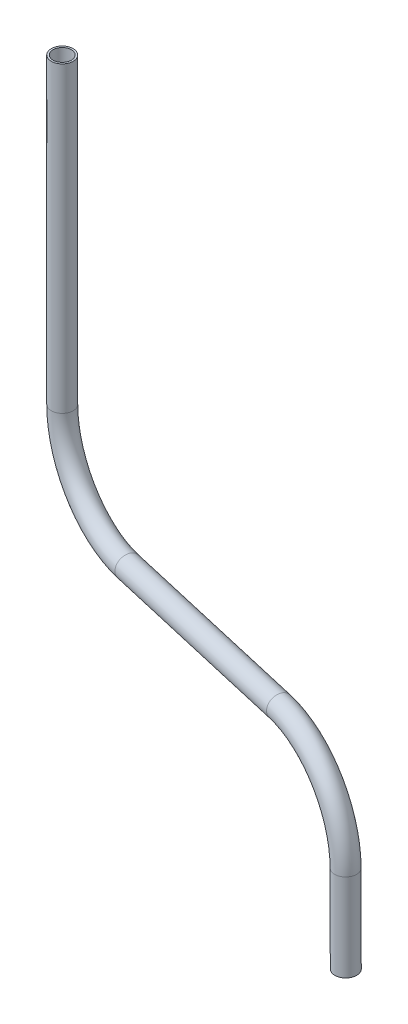
SolidWorks part; units mm, degrees
ref_plane "Front Plane" through (0, 0, 0) normal (0, 0, 1) x (1, 0, 0)
ref_plane "Top Plane" through (0, 0, 0) normal (0, 1, 0) x (1, 0, 0)
ref_plane "Right Plane" through (0, 0, 0) normal (1, 0, 0) x (0, 0, -1)
sketch3d "3DSketch1"
  line L0 (-440.4165, 719.3192, 431.8) -> (-440.4165, 543.9906, 431.8)
  line L1 (-390.9083, 493.1906, 443.183) -> (-276.9007, 493.1906, 469.3958)
  line L2 (-227.3743, 442.3906, 480.6995) -> (-227.3561, 391.6937, 480.6204)
  arc A0 (-446.0045, 719.3192, 441.4787) -> (-434.8285, 719.3192, 441.4787) centre (-440.4165, 719.3192, 431.8) ccw construction
  arc A2 (-440.4165, 543.9906, 431.8) -> (-390.9083, 493.1906, 443.183) centre (-390.9083, 543.9906, 443.183) ccw
  arc A3 (-276.9007, 493.1906, 469.3958) -> (-227.3743, 442.3906, 480.6995) centre (-276.8825, 442.3906, 469.3165) ccw
  point P5 (-440.4165, 730.4952, 431.8)
  point P9 (-440.4165, 493.1906, 431.8)
  point P10 (-402.2913, 543.9906, 492.6913)
  point P11 (0, 0, 0)
  point P12 (-227.3561, 391.6937, 480.6204)
  point P17 (-265.4995, 442.472, 419.8083)
  point P18 (-222.1765, 390.7696, 480.6204)
  point P20 (-222.2532, 394.6852, 480.7861)
  point P21 (0, 0, 0)
  point P22 (0, 0, 0)
  point P23 (-227.7499, 390.7298, 479.3769)
  point P24 (-222.1831, 391.6937, 480.6204)
  point P25 (0, 0, 0)
  point P27 (-222.1765, 390.7696, 480.6204)
  point P30 (0, 0, 0)
  point P31 (0, 0, 0)
  point P32 (0, 0, 0)
  point P33 (-228.0817, 493.1906, 480.6204)
  point P34 (0, 0, 0)
  point P35 (-228.0817, 493.1906, 480.6204)
  point P36 (-228.0817, 493.1906, 480.6204)
  point P37 (-228.0817, 493.1906, 480.6204)
  dimension "D1" = 50.8
  dimension "D2" = 50.8
other "Pipe 0.5 SCH 40(1)"
ref_plane "Plane1" through (-440.4165, 719.3192, 431.8) normal (0, -1, 0) x (1, 0, 0)
sketch "Sketch1" plane through (-440.4165, 719.3192, 431.8) normal (0, -1, 0) x (1, 0, 0)
  circle A0 centre (0, 0) radius 5.2832
  circle A1 centre (0, 0) radius 6.35
  point P5 (0, 0)
  dimension "In_dia" = 10.5664
  dimension "Out_dia" = 12.7
